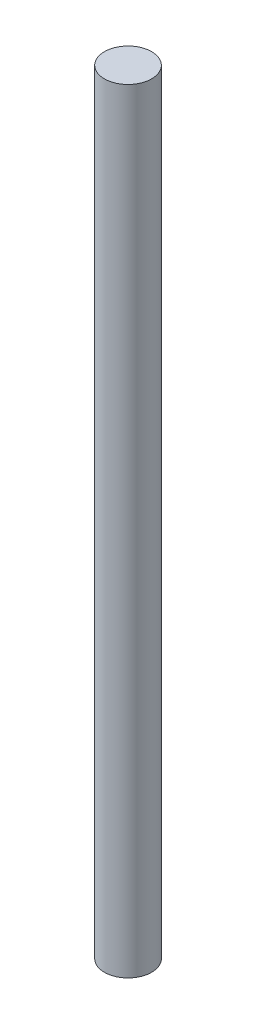
SolidWorks part; units mm, degrees
ref_plane "Front Plane" through (0, 0, 0) normal (0, 0, 1) x (1, 0, 0)
ref_plane "Top Plane" through (0, 0, 0) normal (0, 1, 0) x (1, 0, 0)
ref_plane "Right Plane" through (0, 0, 0) normal (1, 0, 0) x (0, 0, -1)
sketch "Sketch1" plane through (0, 0, 0) normal (0, 0, 1) x (1, 0, 0)
  line L0 (0, -200) -> (0, 100) construction
  line L1 (0, -100) -> (0, -18)
  line L2 (0, -18) -> (2.5, -18)
  line L3 (2.5, -18) -> (2.5, -100)
  line L4 (2.5, -100) -> (0, -100)
revolve "Revolve1" add sketch "Sketch1" angle 360 about L0
